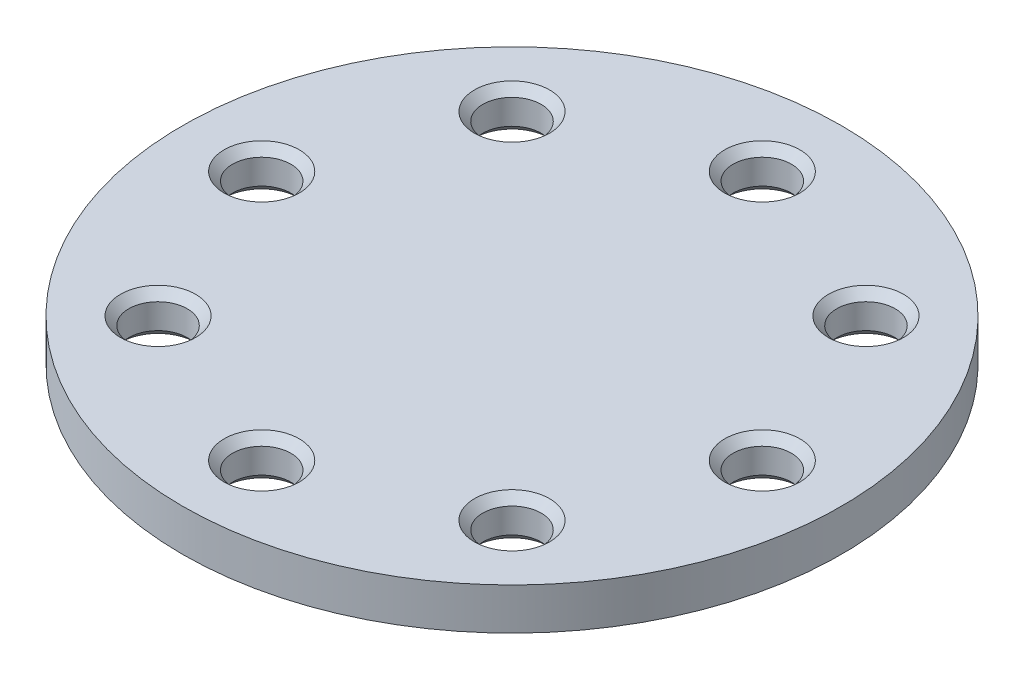
SolidWorks part; units mm, degrees
ref_plane "Plano frontal" through (0, 0, 0) normal (0, 0, 1) x (1, 0, 0)
ref_plane "Plano superior" through (0, 0, 0) normal (0, 1, 0) x (1, 0, 0)
ref_plane "Plano direito" through (0, 0, 0) normal (1, 0, 0) x (0, 0, -1)
sketch "Esboço1" plane through (0, 0, 0) normal (0, 1, 0) x (1, 0, 0)
  circle A0 centre (0, 0) radius 39.5
  circle A1 centre (0, 30) radius 3.5
  circle A2 centre (30, 0) radius 3.5
  circle A3 centre (0, -30) radius 3.5
  circle A4 centre (-30, 0) radius 3.5
  circle A5 centre (21.2132, 21.2132) radius 3.5
  circle A6 centre (30, 0) radius 3.5
  circle A7 centre (21.2132, -21.2132) radius 3.5
  circle A8 centre (0, -30) radius 3.5
  circle A9 centre (-21.2132, -21.2132) radius 3.5
  circle A10 centre (-30, 0) radius 3.5
  circle A11 centre (-21.2132, 21.2132) radius 3.5
  point P14 (0, 0)
  point P29 (0, 0)
  dimension "D1" = 79
  dimension "D2" = 7
  dimension "D3" = 30
  dimension "D4" = 4
  dimension "D5" = 8
extrude "Ressalto-extrusão1" add sketch "Esboço1" along normal blind 5 contours A0 A11 A9 A7 A5 A4 A3 A2 A1
chamfer "Chanfro1" distance 1 angle 45 16 edges at (-30, 5, 3.5) (-30, 0, 3.5) (30, 5, 3.5) (30, 0, 3.5) (0, 5, -26.5) (0, 0, -26.5) (0, 5, 33.5) (0, 0, 33.5) (21.2132, 0, 24.7132) (21.2132, 5, 24.7132) (21.2132, 0, -17.7132) (-21.2132, 0, -17.7132) (-21.2132, 0, 24.7132) (-21.2132, 5, 24.7132) (21.2132, 5, -17.7132) (-21.2132, 5, -17.7132)
sketch "Esboço2" plane through (0, 0, 0) normal (0, -1, 0) x (1, 0, 0)
  circle A0 centre (0, 0) radius 3.9088
